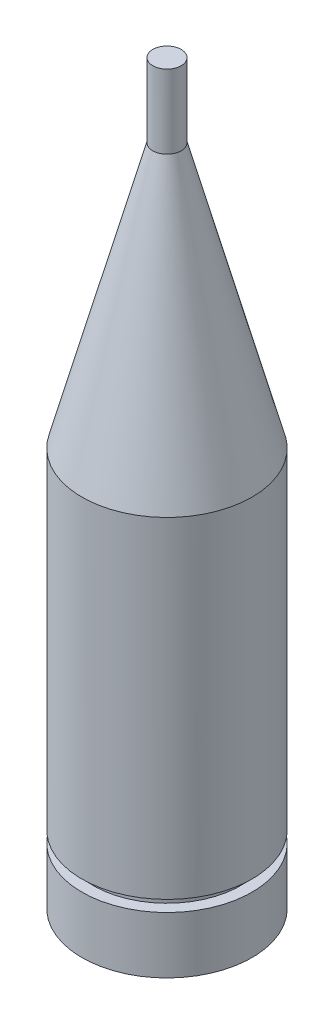
SolidWorks part; units mm, degrees
ref_plane "Alzado" through (0, 0, 0) normal (0, 0, 1) x (1, 0, 0)
ref_plane "Planta" through (0, 0, 0) normal (0, 1, 0) x (1, 0, 0)
ref_plane "Vista lateral" through (0, 0, 0) normal (1, 0, 0) x (0, 0, -1)
sketch "Croquis1" plane through (0, 0, 0) normal (0, 0, 1) x (1, 0, 0)
  line L0 (0, 130) -> (0, 0)
  line L1 (0, 0) -> (15, 0)
  line L2 (15, 0) -> (15, 10)
  line L3 (15, 10) -> (13, 10)
  line L4 (13, 10) -> (13, 12)
  line L5 (13, 12) -> (15, 12)
  line L6 (15, 12) -> (15, 70.3494)
  line L7 (15, 70.3494) -> (2.5, 117)
  line L8 (2.5, 117) -> (2.5, 130)
  line L9 (2.5, 130) -> (0, 130)
  point P3 (0, 0)
  point P12 (0, 0)
  point P13 (3.7869, -3.6182)
  point P14 (7.6657, -29.0577)
  point P15 (28.9381, -14.2535)
  point P16 (27.9434, 4.6018)
  point P17 (13, -92.6551)
  point P18 (13, -115.7789)
  point P19 (13, -115.615)
  point P20 (0, 0)
  point P21 (15, 106.4973)
  point P22 (2.5, 140.6602)
  dimension "D1" = 2.5
  dimension "D2" = 130
  dimension "D3" = 2
  dimension "D4" = 2
  dimension "D5" = 15
  dimension "D6" = 15
  dimension "D7" = 10
  dimension "D8" = 13
revolve "Revolución1" add sketch "Croquis1" angle 360 about L0
